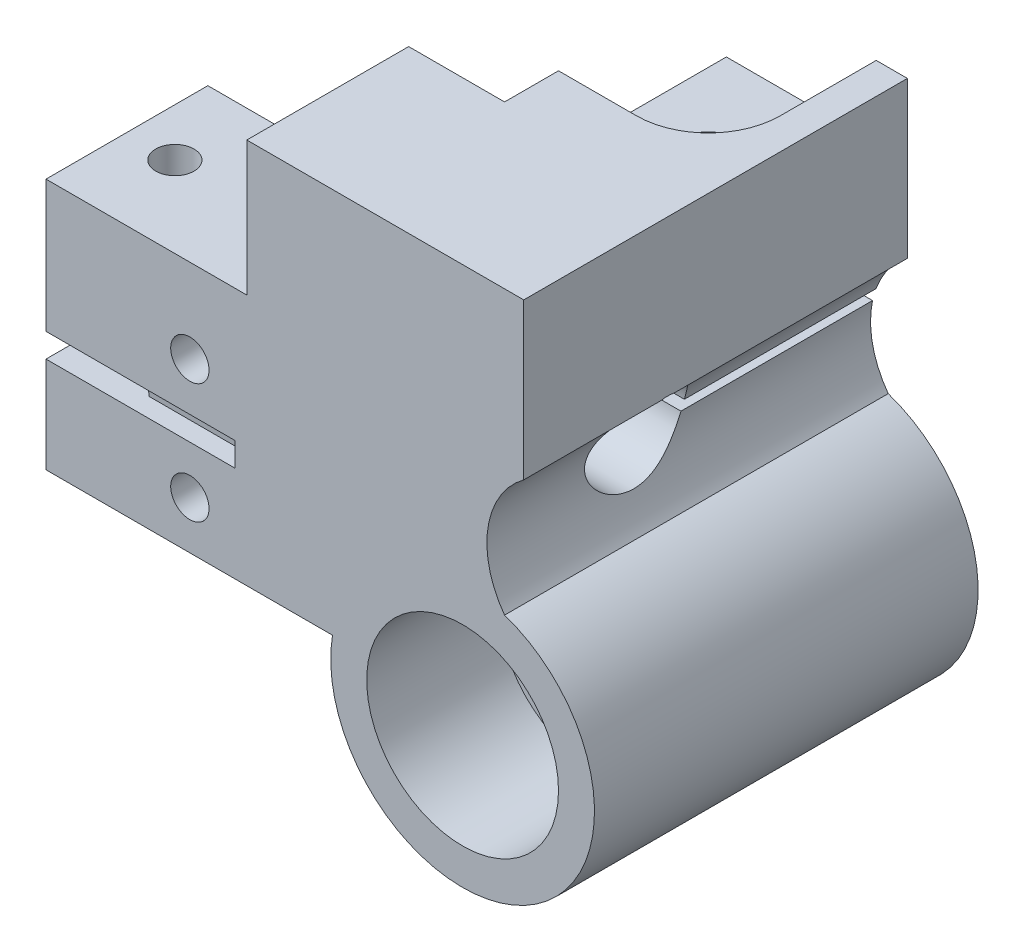
SolidWorks part; units mm, degrees
material "ABS"
ref_plane "Front Plane" through (0, 0, 0) normal (0, 0, 1) x (1, 0, 0)
ref_plane "Top Plane" through (0, 0, 0) normal (0, 1, 0) x (1, 0, 0)
ref_plane "Right Plane" through (0, 0, 0) normal (1, 0, 0) x (0, 0, -1)
sketch "Sketch1" plane through (0, 0, 0) normal (0, 0, 1) x (1, 0, 0)
  line L0 (5.1, 34) -> (5.1, 21)
  line L1 (5.1, 34) -> (-18, 34)
  line L2 (-18, 34) -> (-18, 22.8)
  line L3 (-18, 22.8) -> (-34.75, 22.8)
  line L4 (-34.75, 22.8) -> (-34.75, 11.8)
  line L5 (-34.75, 11.8) -> (-19, 11.8)
  line L6 (-19, 11.8) -> (-19, 9.8)
  line L7 (-19, 9.8) -> (-34.75, 9.8)
  line L8 (-34.75, 9.8) -> (-34.75, 1.8)
  line L9 (-34.75, 1.8) -> (-10.8517, 1.8)
  line L10 (5.1, 21) -> (3.5, 21) construction
  line L11 (3.5, 21) -> (3.5, 10.4283) construction
  line L12 (3.5, 10.4283) -> (9.5858, 14.9142) construction
  line L13 (9.5858, 14.9142) -> (5.1, 21) construction
  arc A0 (-10.8517, 1.8) -> (3.5, 10.4283) centre (0, 0) ccw
  arc A1 (3.5, 10.4283) -> (5.1, 21) centre (9.5858, 14.9142) cw
  dimension "D1" = 22
  dimension "D2" = 34
  dimension "D3" = 13
  dimension "D4" = 5.1
  dimension "D5" = 1.6
  dimension "D6" = 11.2
  dimension "D7" = 23.1
  dimension "D8" = 11
  dimension "D9" = 2
  dimension "D10" = 21
  dimension "D11" = 15.75
  dimension "D12" = 16.75
extrude "Boss-Extrude1" add sketch "Sketch1" along normal mid plane 32
sketch "Sketch2" plane through (0, 0, -16) normal (0, 0, -1) x (-1, 0, 0)
  line L0 (18, 34) -> (10, 34)
  line L1 (-5.1, 34) -> (18, 34) construction
  line L2 (10, 34) -> (10, 4.5826)
  line L4 (10.8517, 1.8) -> (34.75, 1.8)
  line L5 (34.75, 1.8) -> (34.75, 22.8)
  line L6 (34.75, 22.8) -> (18, 22.8)
  line L7 (18, 22.8) -> (18, 34)
  arc A0 (10.8517, 1.8) -> (10, 4.5826) centre (0, 0) ccw
  arc A1 (-3.5, 10.4283) -> (10.8517, 1.8) centre (0, 0) ccw construction
  dimension "D1" = 8
extrude "Cut-Extrude1" cut sketch "Sketch2" against normal offset from surface (18.5 mm away) 13.5 contours L0 L2 A0 L4 L5 L6 L7 up to face at (-16.9165, 14.7182, 16)
sketch "Sketch3" plane through (0, 0, 16) normal (0, 0, 1) x (1, 0, 0)
  circle A0 centre (0, 0) radius 8
  dimension "D1" = 16
extrude "Cut-Extrude2" cut sketch "Sketch3" against normal blind 11
mirror "Mirror1" about plane through (0, 0, 0) normal (0, 0, 1) of "Cut-Extrude2"
sketch "Sketch4" plane through (0, 0, 5) normal (0, 0, 1) x (1, 0, 0)
  circle A0 centre (0, 0) radius 5.75
  dimension "D1" = 11.5
extrude "Cut-Extrude3" cut sketch "Sketch4" against normal up to surface (10 mm away) up to face at (8, 0, -5)
sketch "Sketch5" plane through (5.1, 0, 0) normal (1, 0, 0) x (0, 0, -1)
  line L0 (-4, 17) -> (16, 17) construction
  line L1 (16, 10.4283) -> (16, 21) construction
  line L2 (16, 17.5) -> (16, 16.5)
  line L3 (16, 17.5) -> (0.019, 17.5)
  line L4 (16, 16.5) -> (0.019, 16.5)
  line L5 (-16, 21) -> (-16, 34) construction
  arc A0 (0.019, 17.5) -> (0.019, 16.5) centre (-4, 17) ccw
  point P8 (16, 17)
  dimension "D2" = 8.1
  dimension "D1" = 17
  dimension "D3" = 1
  dimension "D4" = 12
extrude "Cut-Extrude4" cut sketch "Sketch5" against normal blind 17.5
sketch "Sketch6" plane through (0, 0, 16) normal (0, 0, 1) x (1, 0, 0)
  line L0 (-22.75, 15.8) -> (-22.75, 5.8) construction
  line L1 (-34.75, 22.8) -> (-34.75, 11.8) construction
  line L2 (-34.75, 1.8) -> (-10.8517, 1.8) construction
  circle A0 centre (-22.75, 15.8) radius 1.6
  circle A1 centre (-22.75, 5.8) radius 1.6
  dimension "D2" = 3.2
  dimension "D4" = 4
  dimension "D1" = 12
  dimension "D3" = 10
extrude "Cut-Extrude5" cut sketch "Sketch6" against normal through all
sketch "Sketch7" plane through (0, 22.8, 0) normal (0, 1, 0) x (1, 0, 0)
  line L0 (-30.75, -2.5) -> (-30.75, -16) construction
  line L1 (-34.75, -2.5) -> (-18, -2.5) construction
  line L2 (-18, -16) -> (-34.75, -16) construction
  line L3 (-34.75, -16) -> (-34.75, -2.5) construction
  circle A0 centre (-30.75, -9.25) radius 1.6
  dimension "D2" = 3.2
  dimension "D1" = 4
extrude "Cut-Extrude6" cut sketch "Sketch7" against normal up to surface (21 mm away) up to face at (-22.8009, 1.8, 9.25)
sketch "Sketch8" plane through (0, 34, 0) normal (0, 1, 0) x (1, 0, 0)
  line L0 (-10, -2.5) -> (-10, 16) construction
  line L1 (5.1, 16) -> (-10, 16) construction
  circle A0 centre (-3.5, 8) radius 2.6
  dimension "D3" = 5.2
  dimension "D1" = 6.5
  dimension "D2" = 8
extrude "Cut-Extrude7" cut sketch "Sketch8" against normal up to surface (26.8063 mm away)
sketch "Sketch9" plane through (0, 34, 0) normal (0, 1, 0) x (1, 0, 0)
  line L0 (2.5, 8) -> (2.5, 16)
  line L1 (-10, -2.5) -> (-10, 16) construction
  line L2 (-10, 16) -> (-10, 2)
  line L3 (-10, 2) -> (-3.5, 2)
  line L4 (5.1, 16) -> (-10, 16) construction
  line L5 (2.5, 16) -> (-10, 16)
  arc A0 (-3.5, 2) -> (2.5, 8) centre (-3.5, 8) ccw
  dimension "D1" = 6
extrude "Cut-Extrude8" cut sketch "Sketch9" against normal blind 6
sketch "Sketch10" plane through (-19, 0, 0) normal (-1, 0, 0) x (0, 0, 1)
  line L0 (2.5, 11.8) -> (2.6, 10.8)
  line L1 (2.6, 10.8) -> (3.4, 10.8)
  line L2 (3.4, 10.8) -> (3.5, 11.8)
  line L3 (16, 11.8) -> (2.5, 11.8) construction
  line L4 (3.5, 11.8) -> (2.5, 11.8)
  line L5 (3, 11.8) -> (3, 10.8) construction
  dimension "D1" = 1
  dimension "D2" = 1
  dimension "D3" = 0.8
extrude "Boss-Extrude2" add sketch "Sketch10" along normal blind 7.75
pattern_linear "LPattern1" count 7 spacing 2 along (0, 0, 1) of "Boss-Extrude2"
sketch "Sketch11" plane through (0, 0, -16) normal (0, 0, -1) x (-1, 0, 0)
  line L1 (-0.6, 10.3) -> (7.6, 10.3)
  line L2 (-0.6, 10.3) -> (-0.6, 14.5)
  line L3 (-0.6, 14.5) -> (7.6, 14.5)
  line L4 (7.6, 10.3) -> (7.6, 14.5)
  line L5 (-0.6, 10.3) -> (7.6, 14.5) construction
  line L6 (-0.6, 14.5) -> (7.6, 10.3) construction
  line L7 (10, 16.5) -> (10, 4.5826) construction
  line L9 (10, 16.5) -> (-2.1936, 16.5) construction
  point P0 (3.5, 12.4)
  dimension "D1" = 8.2
  dimension "D2" = 4.2
  dimension "D3" = 6.5
  dimension "D4" = 2
extrude "Cut-Extrude9" cut sketch "Sketch11" against normal blind 12.2
